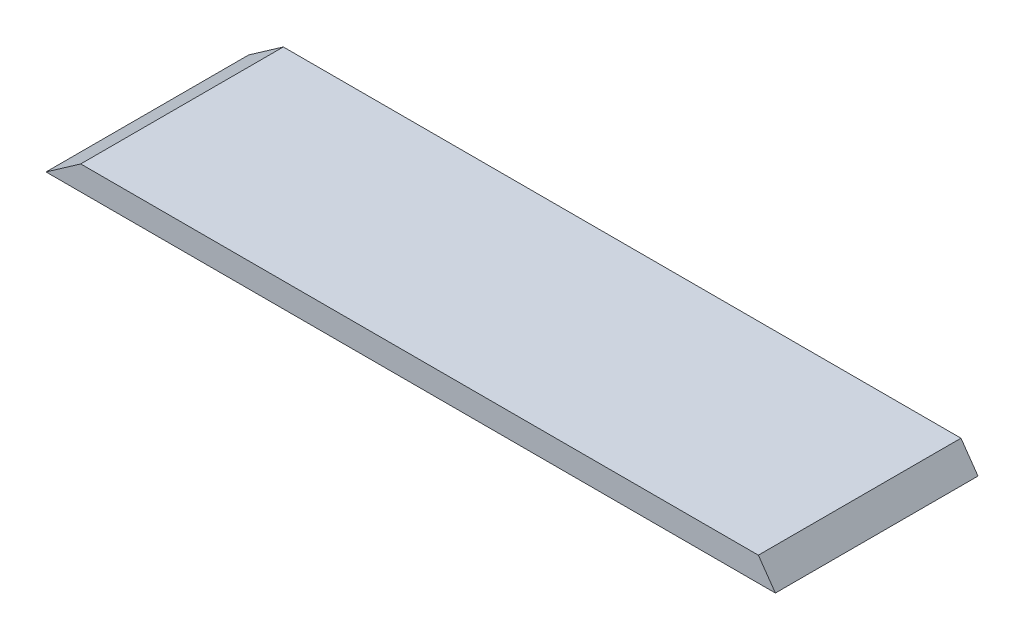
SolidWorks part; units mm, degrees
material "3.3320 (EN-AW 5019)"
ref_plane "Спереди" through (0, 0, 0) normal (0, 0, 1) x (1, 0, 0)
ref_plane "Сверху" through (0, 0, 0) normal (0, 1, 0) x (1, 0, 0)
ref_plane "Справа" through (0, 0, 0) normal (1, 0, 0) x (0, 0, -1)
sketch "Эскиз2" plane through (0, 0, 0) normal (0, 0, 1) x (1, 0, 0)
  line L0 (-45, 0) -> (45, 0)
  line L1 (45, 0) -> (42.8994, 3)
  line L2 (42.8994, 3) -> (-40.7156, 3)
  line L3 (-40.7156, 3) -> (-45, 0)
  line L4 (-45, 0) -> (-45, 51.2905) construction
  line L5 (45, 0) -> (45, 40.4179) construction
  dimension "D1" = 90
  dimension "D2" = 35
  dimension "D3" = 55
  dimension "D4" = 3
extrude "Бобышка-Вытянуть1" add sketch "Эскиз2" along normal blind 25
